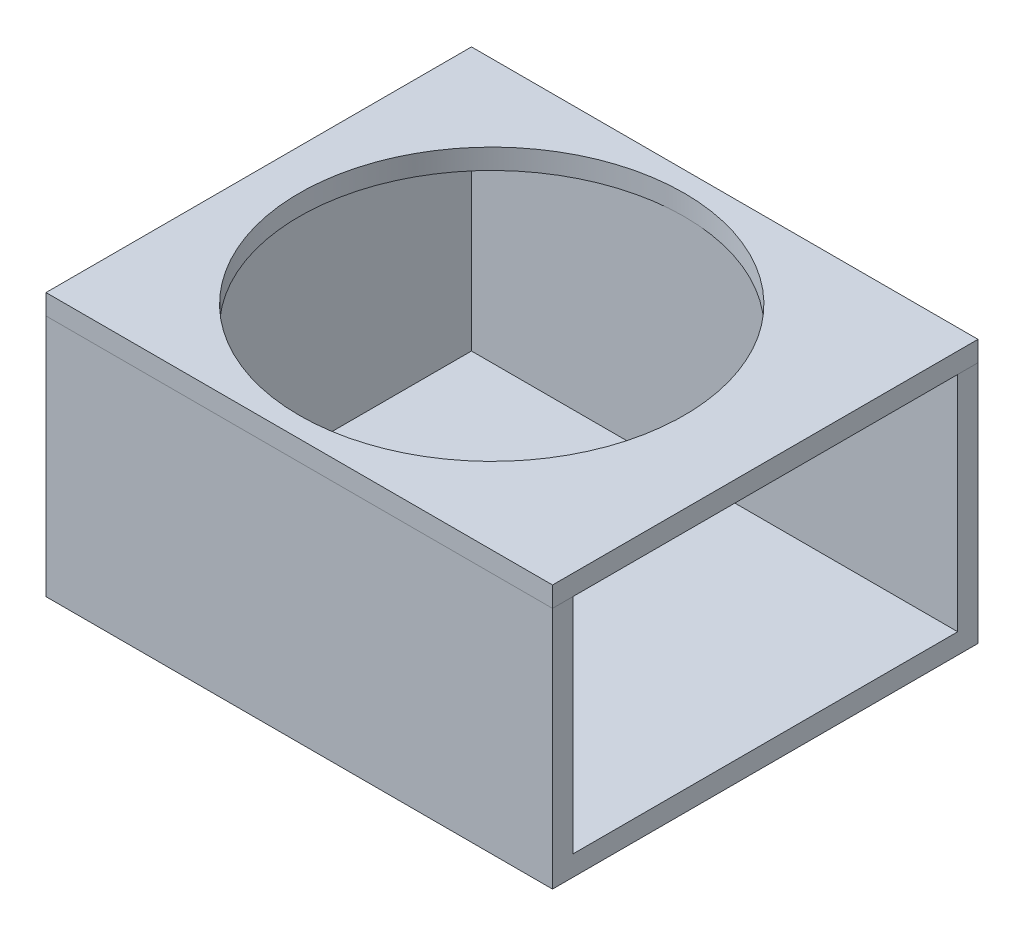
SolidWorks part; units mm, degrees
ref_plane "정면" through (0, 0, 0) normal (0, 0, 1) x (1, 0, 0)
ref_plane "윗면" through (0, 0, 0) normal (0, 1, 0) x (1, 0, 0)
ref_plane "우측면" through (0, 0, 0) normal (1, 0, 0) x (0, 0, -1)
sketch "스케치1" plane through (0, 0, 0) normal (0, 1, 0) x (1, 0, 0)
  line L1 (12.5, -10.5) -> (-12.5, -10.5)
  line L2 (12.5, -10.5) -> (12.5, 10.5)
  line L3 (12.5, 10.5) -> (-12.5, 10.5)
  line L4 (-12.5, -10.5) -> (-12.5, 10.5)
  line L5 (12.5, -10.5) -> (-12.5, 10.5) construction
  line L6 (12.5, 10.5) -> (-12.5, -10.5) construction
  point P0 (0, 0)
  dimension "D1" = 25
  dimension "D2" = 21
extrude "보스-돌출1" add sketch "스케치1" along normal blind 12
sketch "스케치2" plane through (0, 0, 0) normal (0, 1, 0) x (1, 0, 0)
  line L0 (12.5, 10.5) -> (-12.5, 10.5) construction
  line L1 (-11.5, 9.5) -> (13.5, 9.5)
  line L2 (-11.5, 9.5) -> (-11.5, -9.5)
  line L3 (-11.5, -9.5) -> (13.5, -9.5)
  line L4 (13.5, 9.5) -> (13.5, -9.5)
  line L5 (-12.5, 10.5) -> (-12.5, -10.5) construction
  dimension "D1" = 1
  dimension "D2" = 19
  dimension "D3" = 25
  dimension "D4" = 1
extrude "컷-돌출1" cut sketch "스케치2" along normal blind 11 from offset 1
sketch "스케치6" plane through (0, 0, 0) normal (0, 1, 0) x (1, 0, 0)
  line L1 (12.5, -10.5) -> (-12.5, -10.5)
  line L2 (12.5, -10.5) -> (12.5, 10.5)
  line L3 (12.5, 10.5) -> (-12.5, 10.5)
  line L4 (-12.5, -10.5) -> (-12.5, 10.5)
  line L5 (12.5, -10.5) -> (-12.5, 10.5) construction
  line L6 (12.5, 10.5) -> (-12.5, -10.5) construction
  point P0 (0, 0)
extrude "보스-돌출3" add sketch "스케치6" along normal blind 1 from offset 12 separate body
sketch "스케치8" plane through (0, 0, 0) normal (0, 1, 0) x (1, 0, 0)
  line L0 (-12.5, 10.5) -> (-12.5, -10.5) construction
  line L2 (-12.5, -10.5) -> (12.5, -10.5) construction
  circle A0 centre (-1, 0) radius 9.5
  dimension "D1" = 2
  dimension "D2" = 19
  dimension "D3" = 1
extrude "컷-돌출2" cut sketch "스케치8" against normal blind 1 from surface at 13 starting at face at (0, 13, 0)
